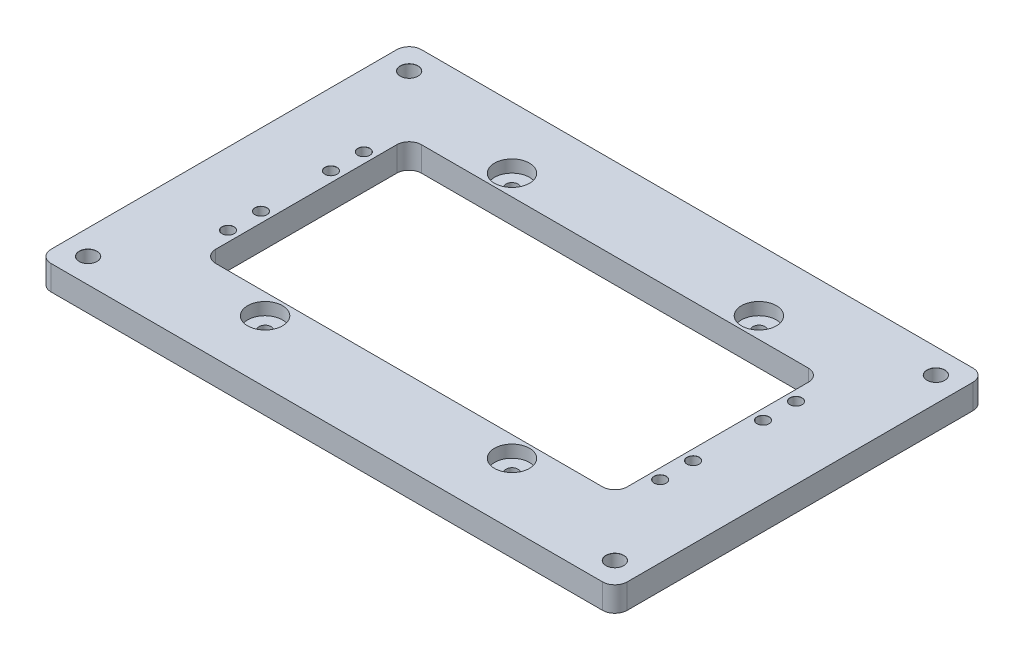
SolidWorks part; units mm, degrees
ref_plane "Front Plane" through (0, 0, 0) normal (0, 0, 1) x (1, 0, 0)
ref_plane "Top Plane" through (0, 0, 0) normal (0, 1, 0) x (1, 0, 0)
ref_plane "Right Plane" through (0, 0, 0) normal (1, 0, 0) x (0, 0, -1)
sketch "Sketch1" plane through (0, 0, 0) normal (0, 1, 0) x (1, 0, 0)
  line L1 (-70, 45) -> (70, 45)
  line L2 (-70, 45) -> (-70, -45)
  line L3 (-70, -45) -> (70, -45)
  line L4 (70, 45) -> (70, -45)
  line L5 (-70, 45) -> (70, -45) construction
  line L6 (-70, -45) -> (70, 45) construction
  point P0 (0, 0)
  dimension "D1" = 90
  dimension "D2" = 140
extrude "Boss-Extrude1" add sketch "Sketch1" along normal blind 6
fillet "Fillet1" radius 3 4 edges at (-70, 3, -45) (70, 3, -45) (-70, 3, 45) (70, 3, 45)
sketch "Sketch2" plane through (0, 6, 0) normal (0, 1, 0) x (1, 0, 0)
  line L1 (-50, 25) -> (50, 25)
  line L2 (-50, 25) -> (-50, -25)
  line L3 (-50, -25) -> (50, -25)
  line L4 (50, 25) -> (50, -25)
  line L5 (-50, 25) -> (50, -25) construction
  line L6 (-50, -25) -> (50, 25) construction
  point P0 (0, 0)
  dimension "D1" = 100
  dimension "D2" = 50
extrude "Cut-Extrude1" cut sketch "Sketch2" against normal blind 10
fillet "Fillet2" radius 3 4 edges at (-50, 3, 25) (50, 3, 25) (50, 3, -25) (-50, 3, -25)
hole_wizard "Ø2.9 (2.9) Diameter Hole1" positions "Sketch3" profile "Sketch4" hole size "Ø2.9" standard "ISO"
sketch "Sketch3" plane through (0, 6, 0) normal (0, 1, 0) x (1, 0, 0)
  line L1 (-52.5, 12.5) -> (52.5, 12.5)
  line L2 (-52.5, 12.5) -> (-52.5, -12.5)
  line L3 (-52.5, -12.5) -> (52.5, -12.5)
  line L4 (52.5, 12.5) -> (52.5, -12.5)
  line L5 (-52.5, 12.5) -> (52.5, -12.5) construction
  line L6 (-52.5, -12.5) -> (52.5, 12.5) construction
  line L7 (52.5, -16.5) -> (52.5, -8.5) construction
  line L9 (52.5, 16.5) -> (52.5, 8.5) construction
  line L11 (-52.5, 16.5) -> (-52.5, 8.5) construction
  line L13 (-52.5, -8.5) -> (-52.5, -16.5) construction
  point P1 (0, 0)
  point P62 (-52.5, 16.5)
  point P64 (-52.5, 8.5)
  point P66 (-52.5, -8.5)
  point P68 (-52.5, -16.5)
  point P70 (52.5, 16.5)
  point P72 (52.5, 8.5)
  point P74 (52.5, -8.5)
  point P76 (52.5, -16.5)
  point P85 (-52.5, 16.5)
  dimension "D1" = 25
  dimension "D2" = 105
  dimension "D3" = 8
sketch "Sketch4" plane through (0, 6, 0) normal (1, 0, 0) x (0, 0, 1)
  line L0 (0, 0) -> (0, 15.8712)
  line L1 (0, 15.8712) -> (1.45, 15)
  line L2 (1.45, 15) -> (1.45, 0.025)
  line L3 (1.45, 0.025) -> (1.475, 0)
  line L5 (1.475, 0) -> (0, 0)
  line L6 (-1.45, 0.025) -> (-1.475, 0) construction
  line L10 (0, 15.8712) -> (-1.45, 15) construction
  line L11 (0, -6.35) -> (0, 107.95) construction
  dimension "Hole Dia." = 2.9
  dimension "Hole Depth" = 15
  dimension "Near C'Sink Dia." = 2.95
  dimension "Near C'Sink Angle" = 90
  dimension "Drill Angle" = 118
hole_wizard "Ø2.9 (2.9) Diameter Hole2" positions "Sketch5" profile "Sketch6" hole size "Ø2.9" standard "ISO"
sketch "Sketch5" plane through (0, 6, 0) normal (0, 1, 0) x (1, 0, 0)
  line L1 (-30, 30) -> (30, 30)
  line L2 (-30, 30) -> (-30, -30)
  line L3 (-30, -30) -> (30, -30)
  line L4 (30, 30) -> (30, -30)
  line L5 (-30, 30) -> (30, -30) construction
  line L6 (-30, -30) -> (30, 30) construction
  point P1 (0, 0)
  point P2 (30, -30)
  point P47 (-30, 30)
  point P48 (-30, -30)
  point P49 (30, 30)
  dimension "D1" = 60
  dimension "D2" = 60
sketch "Sketch6" plane through (0, 6, 0) normal (1, 0, 0) x (0, 0, 1)
  line L0 (0, 0) -> (0, 15.8712)
  line L1 (0, 15.8712) -> (1.45, 15)
  line L2 (1.45, 15) -> (1.45, 0.025)
  line L3 (1.45, 0.025) -> (1.475, 0)
  line L5 (1.475, 0) -> (0, 0)
  line L6 (-1.45, 0.025) -> (-1.475, 0) construction
  line L10 (0, 15.8712) -> (-1.45, 15) construction
  line L11 (0, -6.35) -> (0, 107.95) construction
  dimension "Hole Dia." = 2.9
  dimension "Hole Depth" = 15
  dimension "Near C'Sink Dia." = 2.95
  dimension "Near C'Sink Angle" = 90
  dimension "Drill Angle" = 118
sketch "Sketch7" plane through (0, 6, 0) normal (0, 1, 0) x (1, 0, 0)
  circle A0 centre (-30, 30) radius 4.25
  circle A1 centre (30, 30) radius 4.25
  circle A2 centre (30, -30) radius 4.25
  circle A3 centre (-30, -30) radius 4.25
  dimension "D1" = 8.5
extrude "Cut-Extrude2" cut sketch "Sketch7" against normal blind 3
hole_wizard "Ø4.3 (4.3) Diameter Hole1" positions "Sketch9" profile "Sketch10" hole size "Ø4.3" standard "ISO"
sketch "Sketch9" plane through (0, 6, 0) normal (0, 1, 0) x (1, 0, 0)
  line L1 (-64, 39) -> (64, 39)
  line L2 (-64, 39) -> (-64, -39)
  line L3 (-64, -39) -> (64, -39)
  line L4 (64, 39) -> (64, -39)
  line L5 (-64, 39) -> (64, -39) construction
  line L6 (-64, -39) -> (64, 39) construction
  point P1 (0, 0)
  point P2 (64, -39)
  point P55 (-64, 39)
  point P56 (-64, -39)
  point P57 (64, 39)
  dimension "D1" = 78
  dimension "D2" = 128
sketch "Sketch10" plane through (0, 6, 0) normal (1, 0, 0) x (0, 0, 1)
  line L0 (0, 0) -> (0, 16.2919)
  line L1 (0, 16.2919) -> (2.15, 15)
  line L2 (2.15, 15) -> (2.15, 0.025)
  line L3 (2.15, 0.025) -> (2.175, 0)
  line L5 (2.175, 0) -> (0, 0)
  line L6 (-2.15, 0.025) -> (-2.175, 0) construction
  line L10 (0, 16.2919) -> (-2.15, 15) construction
  line L11 (0, -6.35) -> (0, 107.95) construction
  dimension "Hole Dia." = 4.3
  dimension "Hole Depth" = 15
  dimension "Near C'Sink Dia." = 4.35
  dimension "Near C'Sink Angle" = 90
  dimension "Drill Angle" = 118
